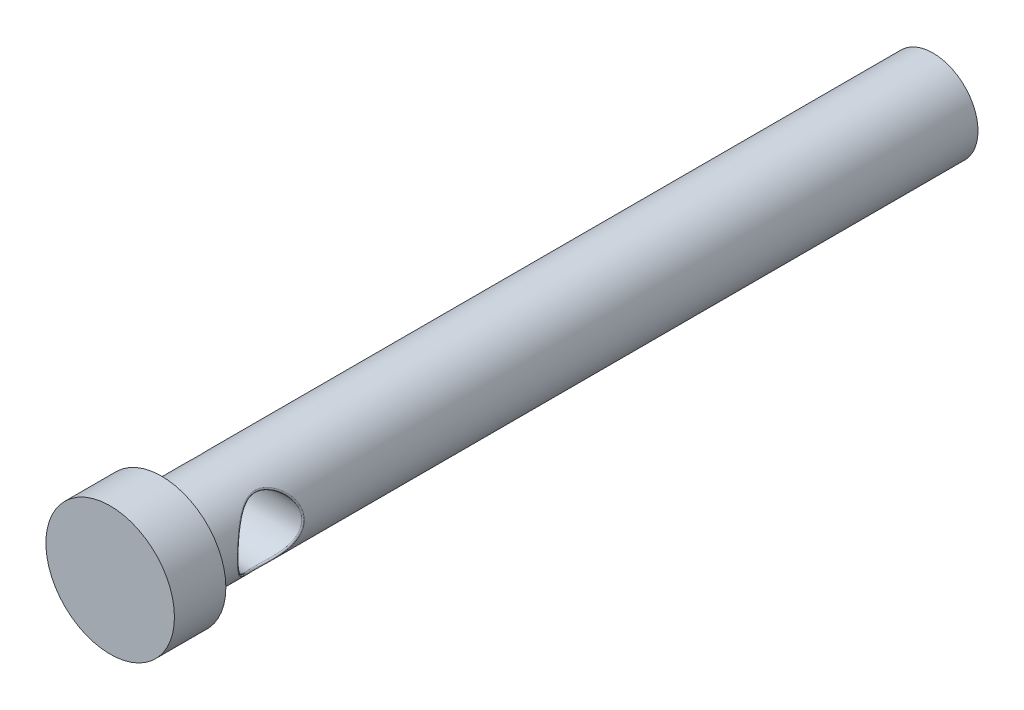
SolidWorks part; units mm, degrees
ref_plane "Front Plane" through (0, 0, 0) normal (0, 0, 1) x (1, 0, 0)
ref_plane "Top Plane" through (0, 0, 0) normal (0, 1, 0) x (1, 0, 0)
ref_plane "Right Plane" through (0, 0, 0) normal (1, 0, 0) x (0, 0, -1)
sketch "Sketch1" plane through (0, 0, 0) normal (0, 0, 1) x (1, 0, 0)
  circle A0 centre (0, 0) radius 3.5
  dimension "D1" = 7
extrude "Boss-Extrude3" add sketch "Sketch1" along normal blind 60
sketch "Sketch3" plane through (0, 0, 60) normal (0, 0, 1) x (1, 0, 0)
  circle A0 centre (0, 0) radius 5
extrude "Boss-Extrude4" add sketch "Sketch3" along normal blind 4
sketch "Sketch4" plane through (0, 0, 0) normal (1, 0, 0) x (0, 0, -1)
  circle A0 centre (-55, 0) radius 2.5
  dimension "D2" = 5
extrude "Cut-Extrude1" cut sketch "Sketch4" against normal mid plane 282
fillet "Fillet3" radius 0.1 1 edges at (3.4693, 0.4623, 57.4569)
fillet "Fillet4" radius 0.1 1 edges at (-3.4693, 0.4623, 52.5431)
